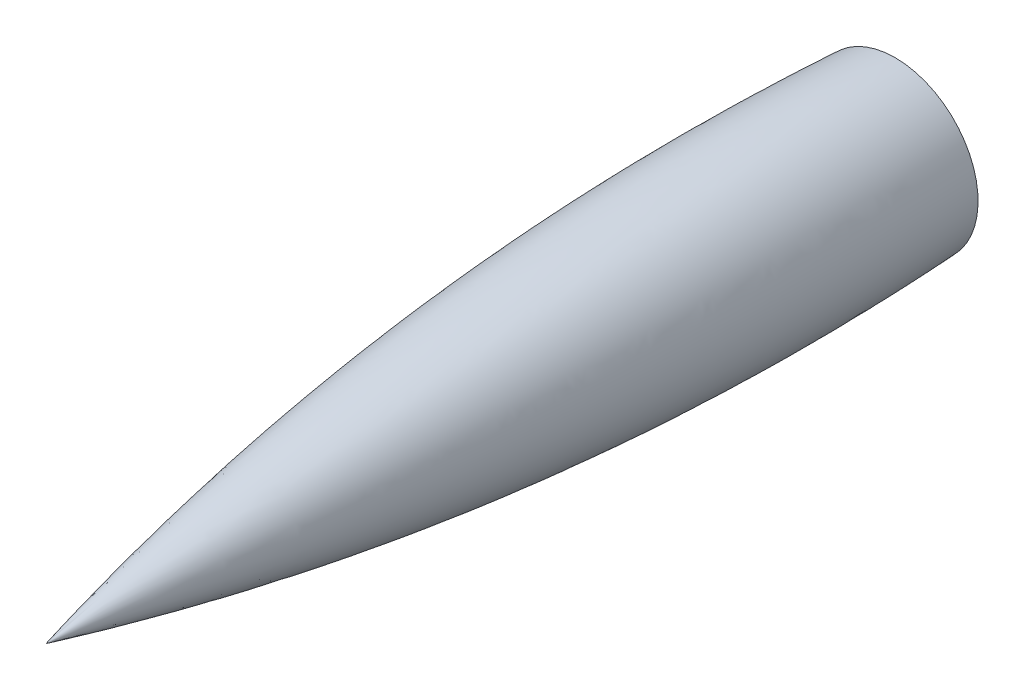
SolidWorks part; units mm, degrees
ref_plane "Front Plane" through (0, 0, 0) normal (0, 0, 1) x (1, 0, 0)
ref_plane "Top Plane" through (0, 0, 0) normal (0, 1, 0) x (1, 0, 0)
ref_plane "Right Plane" through (0, 0, 0) normal (1, 0, 0) x (0, 0, -1)
sketch "Sketch1" plane through (0, 0, 0) normal (1, 0, 0) x (0, 0, -1)
  line L0 (0, 50.8) -> (0, 0)
  line L1 (0, 0) -> (-520.7308, 0)
  spline S0 degree 4 poles (-571.0294, -13.4763) (-570.2418, -13.2527) (-568.6665, -12.8066) (-565.5158, -11.9184) (-560.7839, -10.5973) (-555.2626, -9.0742) (-549.7391, -7.5728) (-545.02, -6.3056) (-541.0842, -5.2594) (-537.9751, -4.4387) (-534.8037, -3.6085) (-531.7618, -2.8171) (-528.439, -1.961) (-525.7179, -1.2628) (-521.7347, -0.2526) (-519.8086, 0.233) (-515.9343, 1.2038) (-513.255, 1.8677) (-510.0675, 2.654) (-507.0979, 3.3796) (-504.0303, 4.1242) (-501.0039, 4.8526) (-497.1979, 5.7617) (-492.6375, 6.8395) (-485.7862, 8.4374) (-478.1683, 10.1758) (-470.5403, 11.8784) (-462.9055, 13.5446) (-456.7924, 14.8558) (-449.1456, 16.4676) (-439.9601, 18.3581) (-429.2309, 20.4999) (-416.9517, 22.8603) (-404.6561, 25.1331) (-386.1887, 28.4108) (-352.262, 34.0174) (-308.9191, 40.1261) (-262.2986, 45.2339) (-221.7898, 48.5066) (-196.8328, 50.1056) (-181.2261, 50.9567) (-168.7361, 51.5486) (-156.2423, 52.0514) (-143.7451, 52.4652) (-131.2454, 52.7898) (-118.7436, 53.0254) (-107.8035, 53.1535) (-98.4256, 53.2076) (-90.6109, 53.2156) (-84.3586, 53.1997) (-76.5447, 53.152) (-68.7285, 53.067) (-60.9172, 52.9452) (-53.1001, 52.7858) (-46.8564, 52.6366) (-40.5947, 52.4641) (-35.1476, 52.2953) (-30.4293, 52.1341) (-25.7976, 51.9663) (-21.0006, 51.7786) (-15.7554, 51.5619) (-9.9383, 51.2956) (-5.7848, 51.0971) (-1.0488, 50.8554) (0.9041, 50.753) (4.6169, 50.5531) (7.2979, 50.4024) (10.3379, 50.228) (13.2494, 50.0553) (16.2085, 49.8751) (19.1483, 49.6909) (22.0956, 49.5014) (25.0394, 49.3072) (28.7202, 49.058) (33.1358, 48.7492) (37.5509, 48.428) (41.9649, 48.0944) (44.9071, 47.8654) (46.3781, 47.7492) (47.1135, 47.6908) knots 0 0 0 0 0 0.005243 0.010487 0.020974 0.03146 0.041947 0.047128 0.052308 0.057489 0.06267 0.06785 0.073031 0.078211 0.083392 0.088398 0.093404 0.09841 0.103416 0.108422 0.113428 0.118433 0.123439 0.133451 0.143463 0.163487 0.173499 0.18351 0.193522 0.203534 0.223558 0.243581 0.263605 0.283629 0.303652 0.363723 0.483865 0.56396 0.604007 0.624031 0.644055 0.664078 0.684102 0.704126 0.724149 0.744173 0.764197 0.774209 0.78422 0.794232 0.804244 0.824268 0.83428 0.844291 0.854303 0.864315 0.874327 0.879333 0.884339 0.89435 0.904362 0.914374 0.91938 0.924386 0.929112 0.933838 0.938564 0.943289 0.948015 0.952741 0.957467 0.962193 0.966919 0.971645 0.981096 0.990548 0.995274 1 1 1 1 1 construction
  spline S1 degree 4 poles (-520.7308, 0) (-520.0935, 0.1606) (-518.8149, 0.482) (-515.9343, 1.2038) (-513.255, 1.8677) (-510.0675, 2.654) (-507.0979, 3.3796) (-504.0303, 4.1242) (-501.0039, 4.8526) (-497.1979, 5.7617) (-492.6375, 6.8395) (-485.7862, 8.4374) (-478.1683, 10.1758) (-470.5403, 11.8784) (-462.9055, 13.5446) (-456.7924, 14.8558) (-449.1456, 16.4676) (-439.9601, 18.3581) (-429.2309, 20.4999) (-416.9517, 22.8603) (-404.6561, 25.1331) (-386.1887, 28.4108) (-352.262, 34.0174) (-308.9191, 40.1261) (-262.2986, 45.2339) (-221.7898, 48.5066) (-196.8328, 50.1056) (-181.2261, 50.9567) (-168.7361, 51.5486) (-156.2423, 52.0514) (-143.7451, 52.4652) (-131.2454, 52.7898) (-118.7436, 53.0254) (-107.8035, 53.1535) (-98.4256, 53.2076) (-90.6109, 53.2156) (-84.3586, 53.1997) (-76.5447, 53.152) (-68.7285, 53.067) (-60.9172, 52.9452) (-53.1001, 52.7858) (-46.8564, 52.6366) (-40.5947, 52.4641) (-35.1476, 52.2953) (-30.4293, 52.1341) (-25.7976, 51.9663) (-21.0006, 51.7786) (-15.7554, 51.5619) (-9.9383, 51.2956) (-5.7848, 51.0971) (-1.9531, 50.9016) (-0.6563, 50.8344) (0, 50.8) knots 0.083392 0.083392 0.083392 0.083392 0.083392 0.088398 0.093404 0.09841 0.103416 0.108422 0.113428 0.118433 0.123439 0.133451 0.143463 0.163487 0.173499 0.18351 0.193522 0.203534 0.223558 0.243581 0.263605 0.283629 0.303652 0.363723 0.483865 0.56396 0.604007 0.624031 0.644055 0.664078 0.684102 0.704126 0.724149 0.744173 0.764197 0.774209 0.78422 0.794232 0.804244 0.824268 0.83428 0.844291 0.854303 0.864315 0.874327 0.879333 0.884339 0.89435 0.904362 0.914374 0.91938 0.924386 0.924386 0.924386 0.924386 0.924386
  dimension "D1" = 50.8
revolve "Revolve1" add sketch "Sketch1" angle 360 about L1
equation "\"R\"= 2'base radius"
equation "\"L\"= 16.5'overall length"
equation "\"rho\"= ( \"R\" ^ 2 + \"L\" ^ 2 ) / ( 2 * \"R\" )'ogive radius"
equation "\"alpha\"= arccos ( sqr ( \"L\" ^ 2 + \"R\" ^ 2 ) / ( 2 * \"rho\" ) ) - atn ( \"R\" / \"L\" )"
